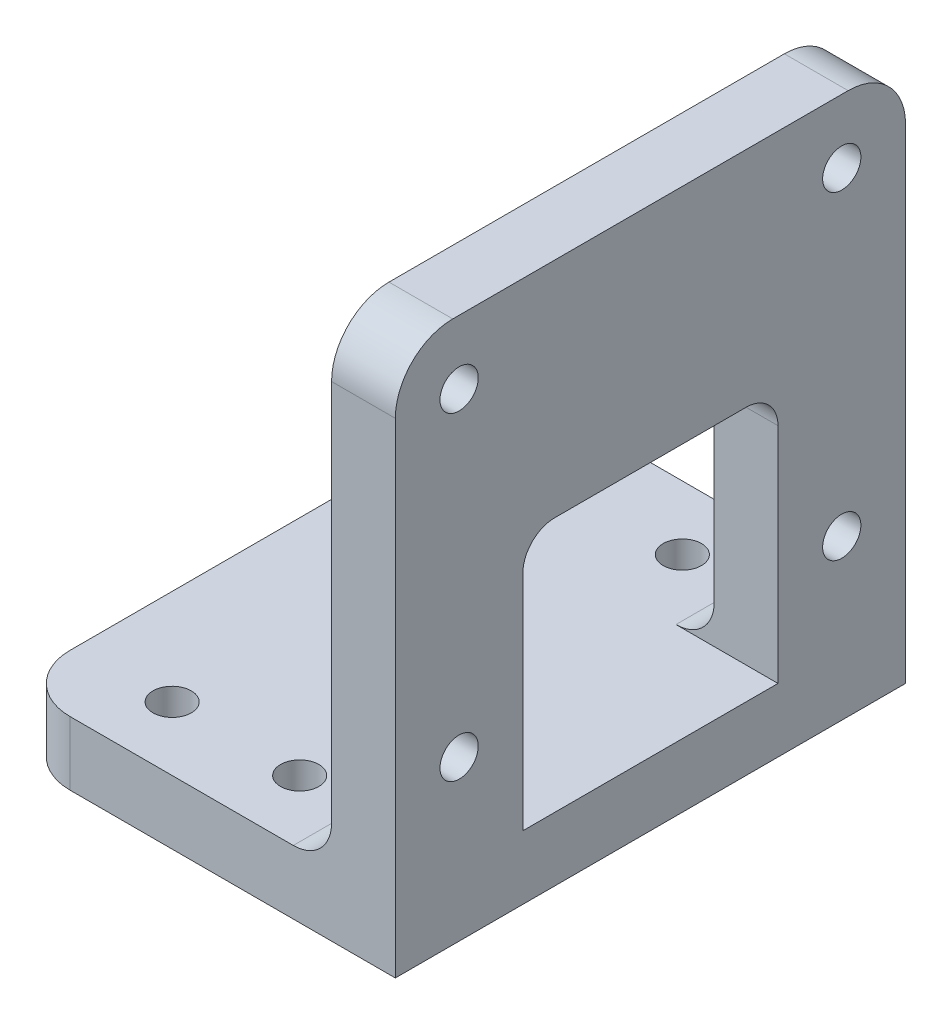
SolidWorks part; units mm, degrees
ref_plane "Front Plane" through (0, 0, 0) normal (0, 0, 1) x (1, 0, 0)
ref_plane "Top Plane" through (0, 0, 0) normal (0, 1, 0) x (1, 0, 0)
ref_plane "Right Plane" through (0, 0, 0) normal (1, 0, 0) x (0, 0, -1)
sketch "Sketch1" plane through (0, 0, 0) normal (0, 1, 0) x (1, 0, 0)
  line L0 (0, 20) -> (25, 20) construction
  line L1 (4.5, 0) -> (25, 0)
  line L2 (0, 4.5) -> (0, 35.5)
  line L3 (4.5, 40) -> (25, 40)
  line L4 (25, 0) -> (25, 40)
  arc A0 (0, 4.5) -> (4.5, 0) centre (4.5, 4.5) ccw
  arc A1 (0, 35.5) -> (4.5, 40) centre (4.5, 35.5) cw
  circle A2 centre (7.5, 35) radius 1.5
  circle A3 centre (17.5, 35) radius 1.5
  circle A4 centre (17.5, 5) radius 1.5
  circle A5 centre (7.5, 5) radius 1.5
  point P7 (0, 0)
  point P10 (0, 40)
  point P17 (0, 0)
  dimension "D3" = 4.5
  dimension "D4" = 3
  dimension "D1" = 40
  dimension "D2" = 25
  dimension "D5" = 10
  dimension "D6" = 7.5
  dimension "D7" = 15
extrude "Boss-Extrude1" add sketch "Sketch1" along normal blind 5
ref_plane "Plane1" through (25, 0, 0) normal (1, 0, 0) x (0, 0, -1)
sketch "Sketch2" plane through (25, 0, 0) normal (1, 0, 0) x (0, 0, -1)
  line L0 (0, 0) -> (40, 0) construction
  line L1 (0, 0) -> (40, 0)
  line L2 (0, 0) -> (0, 38)
  line L3 (4.5, 42.5) -> (35.5, 42.5)
  line L4 (40, 0) -> (40, 38)
  line L5 (20, 42.5) -> (20, 0) construction
  line L6 (5, 12.5) -> (35, 12.5) construction
  line L12 (0, 5) -> (40, 5) construction
  line L13 (27.5, 25) -> (12.5, 25)
  line L14 (20, 25) -> (20, 5) construction
  line L15 (30, 5) -> (10, 5)
  line L16 (10, 22.5) -> (10, 5)
  line L17 (30, 22.5) -> (30, 5)
  arc A0 (40, 38) -> (35.5, 42.5) centre (35.5, 38) ccw
  arc A1 (0, 38) -> (4.5, 42.5) centre (4.5, 38) cw
  circle A3 centre (5, 37.5) radius 1.5
  circle A4 centre (5, 12.5) radius 1.5
  circle A5 centre (35, 12.5) radius 1.5
  circle A6 centre (35, 37.5) radius 1.5
  arc A7 (10, 22.5) -> (12.5, 25) centre (12.5, 22.5) cw
  arc A8 (30, 22.5) -> (27.5, 25) centre (27.5, 22.5) ccw
  point P11 (0, 42.5)
  point P28 (10, 25)
  dimension "D2" = 4.5
  dimension "D3" = 3
  dimension "D9" = 2.5
  dimension "D1" = 42.5
  dimension "D4" = 25
  dimension "D5" = 15
  dimension "D6" = 12.5
  dimension "D7" = 10
  dimension "D8" = 20
extrude "Boss-Extrude3" add sketch "Sketch2" along normal blind 5
fillet "Fillet4" radius 3 2 edges at (25, 5, -5) (25, 5, -35)
